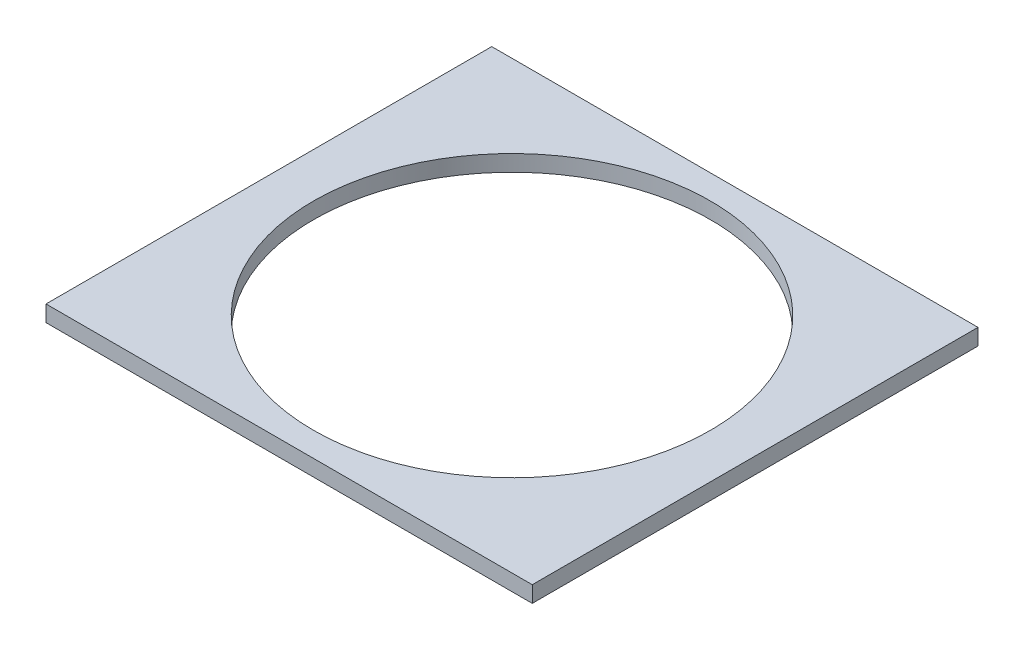
SolidWorks part; units mm, degrees
ref_plane "Ön Düzlem" through (0, 0, 0) normal (0, 0, 1) x (1, 0, 0)
ref_plane "Üst Düzlem" through (0, 0, 0) normal (0, 1, 0) x (1, 0, 0)
ref_plane "Sağ Düzlem" through (0, 0, 0) normal (1, 0, 0) x (0, 0, -1)
sketch "Çizim1" plane through (0, 0, 0) normal (0, 1, 0) x (1, 0, 0)
  line L1 (0, 0) -> (60, 0)
  line L2 (0, 0) -> (0, -55)
  line L3 (0, -55) -> (60, -55)
  line L4 (60, 0) -> (60, -55)
  dimension "D1" = 60
  dimension "D2" = 55
extrude "Yükseklik-Ekstrüzyon1" add sketch "Çizim1" along normal blind 2
sketch "Çizim2" plane through (0, 2, 0) normal (0, 1, 0) x (1, 0, 0)
  circle A0 centre (30, -27.5) radius 24.5
  point P2 (30, -26)
  point P3 (30, -27.5)
  dimension "D1" = 49
extrude "Kes-Ekstrüzyon1" cut sketch "Çizim2" against normal blind 2
